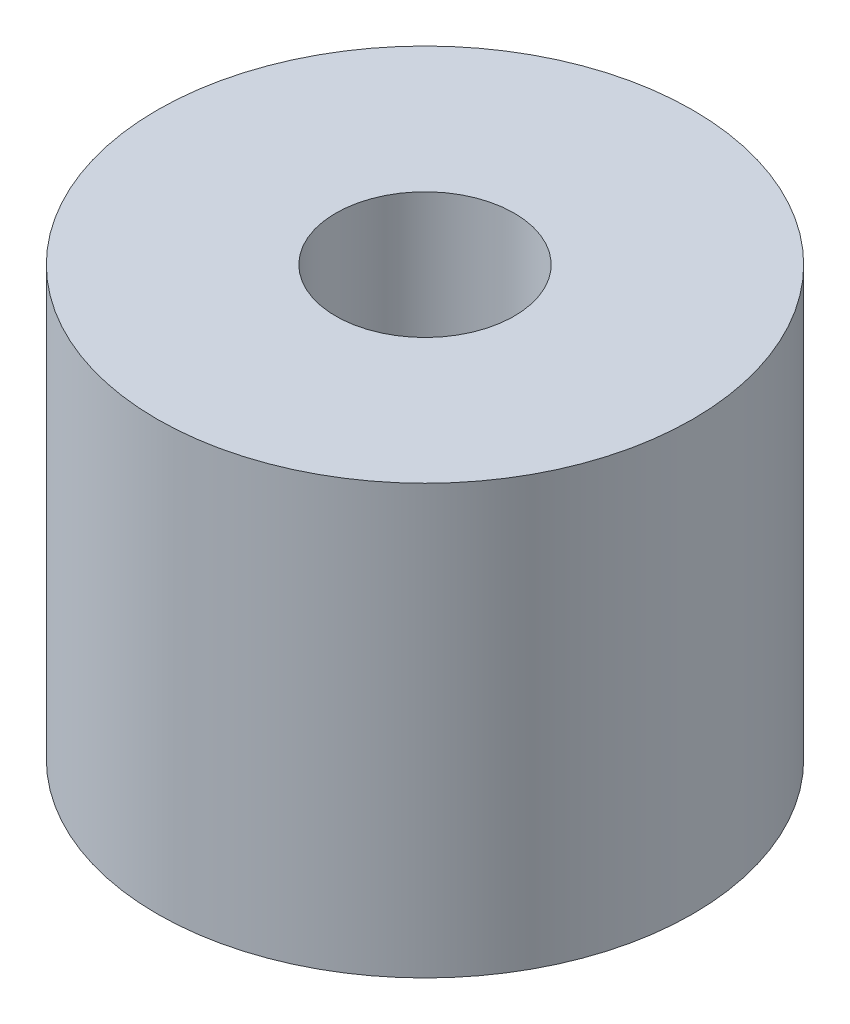
SolidWorks part; units mm, degrees
ref_plane "Front Plane" through (0, 0, 0) normal (0, 0, 1) x (1, 0, 0)
ref_plane "Top Plane" through (0, 0, 0) normal (0, 1, 0) x (1, 0, 0)
ref_plane "Right Plane" through (0, 0, 0) normal (1, 0, 0) x (0, 0, -1)
sketch "Sketch1" plane through (0, 0, 0) normal (0, 1, 0) x (1, 0, 0)
  circle A0 centre (0, 0) radius 1.5875
  circle A1 centre (0, 0) radius 4.7625
  dimension "D1" = 9.525
  dimension "D2" = 3.175
extrude "Boss-Extrude1" add sketch "Sketch1" along normal blind 7.62
